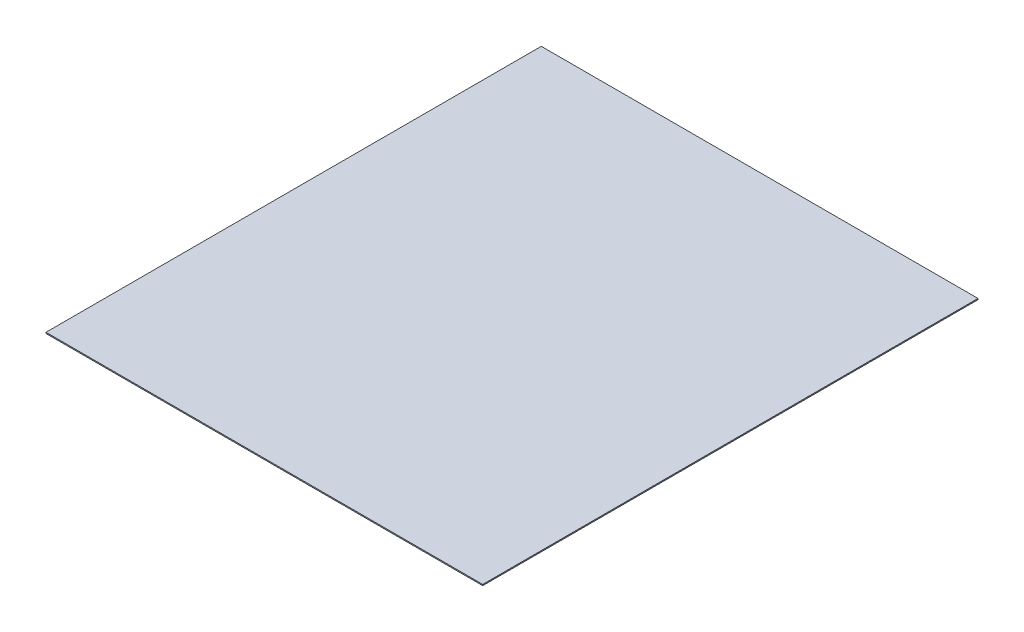
SolidWorks part; units mm, degrees
ref_plane "Front Plane" through (0, 0, 0) normal (0, 0, 1) x (1, 0, 0)
ref_plane "Top Plane" through (0, 0, 0) normal (0, 1, 0) x (1, 0, 0)
ref_plane "Right Plane" through (0, 0, 0) normal (1, 0, 0) x (0, 0, -1)
other "Configuration Table"
sketch "Sketch1" plane through (0, 0, 0) normal (0, 0, 1) x (1, 0, 0)
  line L1 (16.7, 5) -> (601.3, 5)
  line L2 (16.7, 5) -> (16.7, 6.5)
  line L3 (16.7, 6.5) -> (601.3, 6.5)
  line L4 (601.3, 5) -> (601.3, 6.5)
extrude "CEK_1L_tepsi_taban_saci_1.5_1" add sketch "Sketch1" against normal blind 663 from offset 3 separate body
